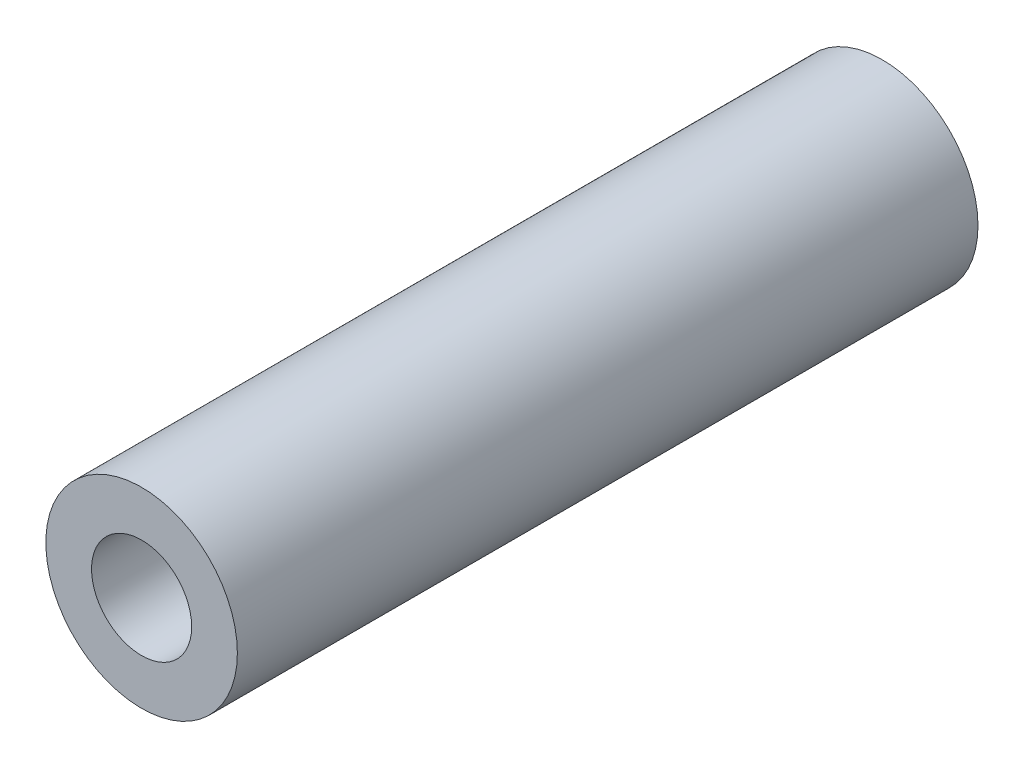
SolidWorks part; units mm, degrees
ref_plane "Front Plane" through (0, 0, 0) normal (0, 0, 1) x (1, 0, 0)
ref_plane "Top Plane" through (0, 0, 0) normal (0, 1, 0) x (1, 0, 0)
ref_plane "Right Plane" through (0, 0, 0) normal (1, 0, 0) x (0, 0, -1)
sketch "Sketch1" plane through (0, 0, 0) normal (0, 0, 1) x (1, 0, 0)
  circle A0 centre (0, 0) radius 4.7625
  circle A1 centre (0, 0) radius 2.4892
  dimension "D1" = 9.525
  dimension "D2" = 4.9784
extrude "Boss-Extrude1" add sketch "Sketch1" along normal mid plane 36.83
